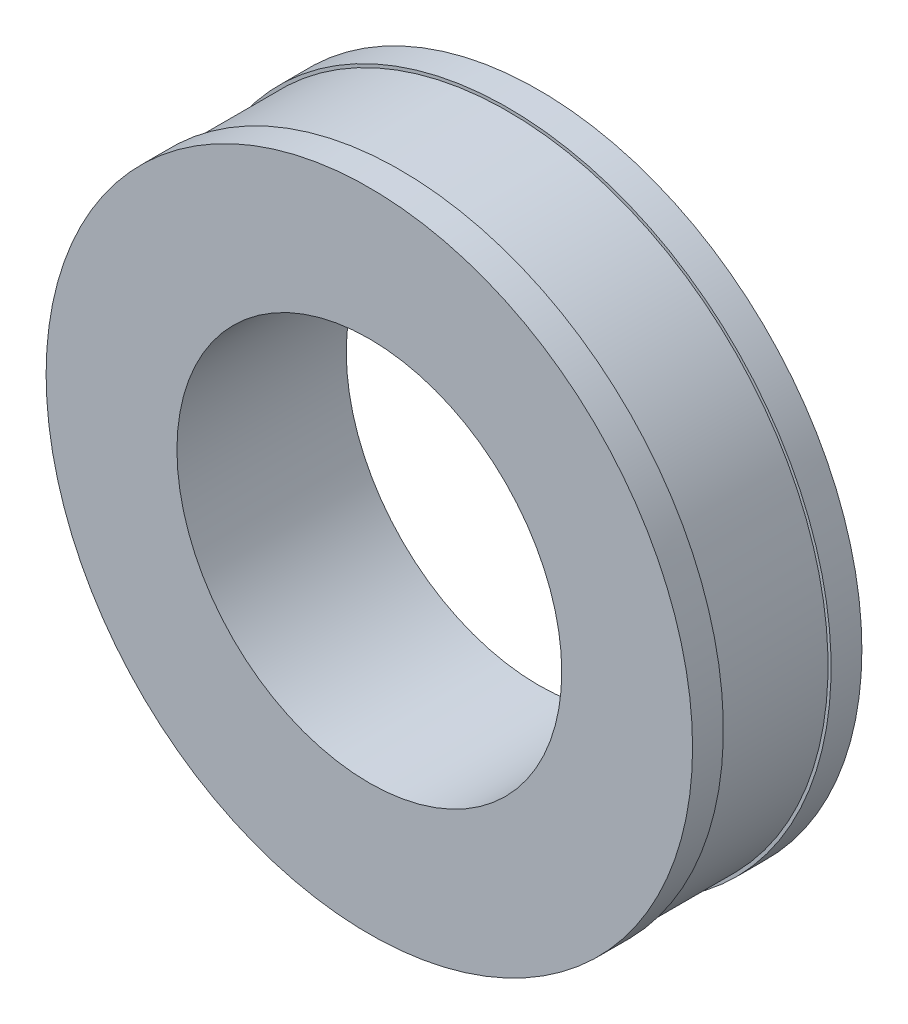
SolidWorks part; units mm, degrees
material "1023 Tôle d'acier au carbone (SS)"
ref_plane "Plan de face" through (0, 0, 0) normal (0, 0, 1) x (1, 0, 0)
ref_plane "Plan de dessus" through (0, 0, 0) normal (0, 1, 0) x (1, 0, 0)
ref_plane "Plan de droite" through (0, 0, 0) normal (1, 0, 0) x (0, 0, -1)
sketch "Esquisse1" plane through (0, 0, 0) normal (0, 0, 1) x (1, 0, 0)
  circle A0 centre (0, 0) radius 12.5
  circle A1 centre (0, 0) radius 21
  dimension "D1" = 25
  dimension "D2" = 42
extrude "Boss.-Extru.1" add sketch "Esquisse1" along normal blind 11
sketch "Esquisse2" plane through (0, 0, 0) normal (0, 1, 0) x (1, 0, 0)
  line L0 (0, 0) -> (0, -11) construction
  line L1 (-21, -11) -> (21, -11) construction
  line L2 (-21, 0) -> (-21, -11) construction
  line L3 (-21, -2) -> (-20.8, -2)
  line L4 (-21, -2) -> (-21, -9)
  line L5 (-21, -9) -> (-20.8, -9)
  line L6 (-20.8, -2) -> (-20.8, -9)
  line L7 (21, 0) -> (-21, 0) construction
  dimension "D1" = 2
  dimension "D2" = 0.2
  dimension "D3" = 2
revolve "Enlèvement de matière-Révolution1" cut sketch "Esquisse2" angle 360 about L0
